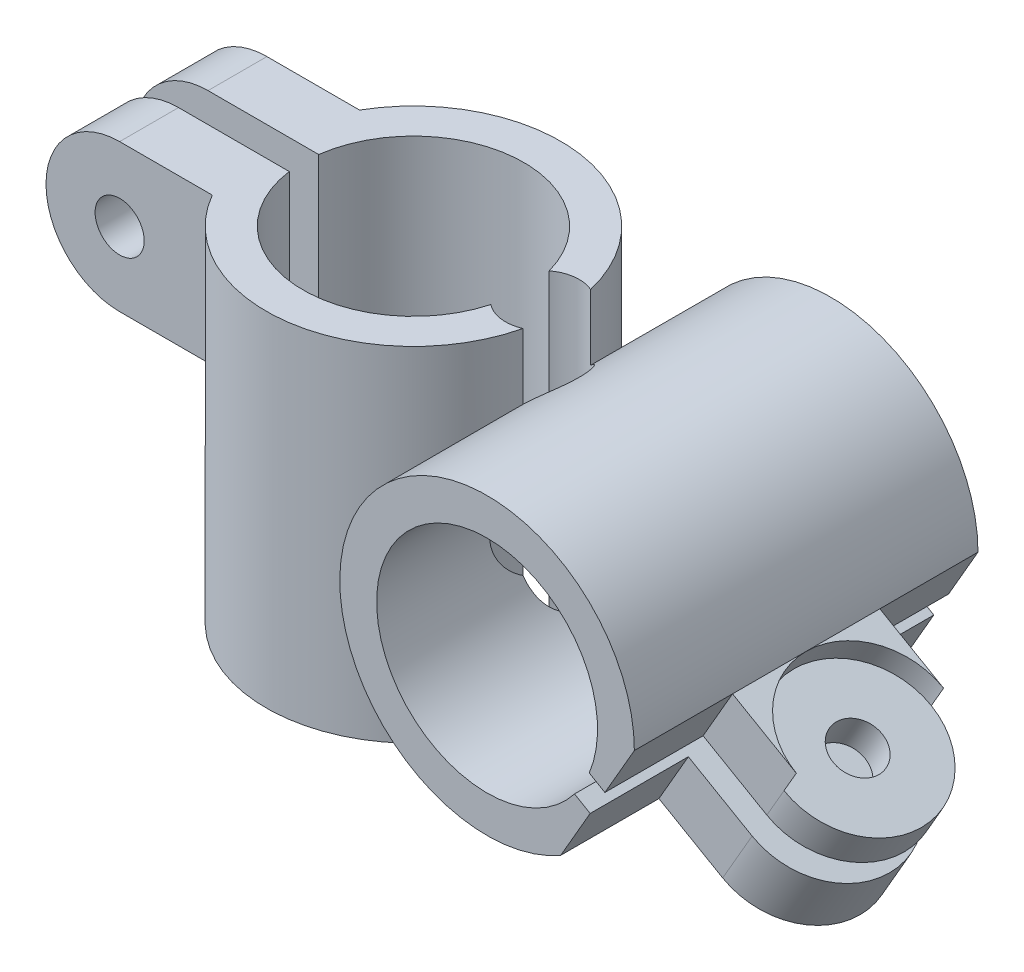
SolidWorks part; units mm, degrees
ref_plane "Front Plane" through (0, 0, 0) normal (0, 0, 1) x (1, 0, 0)
ref_plane "Top Plane" through (0, 0, 0) normal (0, 1, 0) x (1, 0, 0)
ref_plane "Right Plane" through (0, 0, 0) normal (1, 0, 0) x (0, 0, -1)
sketch "Sketch2" plane through (0, 0, 0) normal (0, 1, 0) x (1, 0, 0)
  line L0 (-34.709, 0) -> (31.8786, 0) construction
  line L1 (-29.8496, 3) -> (-22.2991, 3)
  line L2 (-29.8496, -3) -> (-22.2991, -3)
  arc A0 (-22.2991, -3) -> (21.6964, -5.9594) centre (0, 0) ccw
  circle A1 centre (0, 0) radius 26.25 construction
  arc A2 (-29.8496, -3) -> (29.1964, -6.897) centre (0, 0) ccw
  arc A3 (21.6964, -5.9594) -> (29.1964, -6.897) centre (26.25, 0) ccw
  arc A4 (21.6964, 5.9594) -> (-22.2991, 3) centre (0, 0) ccw
  arc A5 (29.1964, 6.897) -> (21.6964, 5.9594) centre (26.25, 0) ccw
  arc A6 (29.1964, 6.897) -> (-29.8496, 3) centre (0, 0) ccw
  dimension "D1" = 45
  dimension "D2" = 52.5
  dimension "D3" = 60
  dimension "D4" = 15
  dimension "D5" = 6
  dimension "D6" = 3
extrude "Boss-Extrude1" add sketch "Sketch2" along normal blind 70
sketch "Sketch3" plane through (0, 0, -3) normal (0, 0, 1) x (1, 0, 0)
  line L0 (-29.8496, 70) -> (-44.8496, 70)
  line L1 (-29.8496, 40) -> (-44.8496, 40)
  line L2 (-29.8496, 70) -> (-29.8496, 0) construction
  line L3 (-29.8496, 70) -> (-29.8496, 40)
  arc A0 (-44.8496, 40) -> (-44.8496, 70) centre (-44.8496, 55) cw
  circle A1 centre (-44.8496, 55) radius 5
  dimension "D1" = 15
  dimension "D3" = 10
  dimension "D2" = 15
extrude "Boss-Extrude3" add sketch "Sketch3" against normal blind 12 separate body
sketch "Sketch4" plane through (0, 0, 3) normal (0, 0, -1) x (-1, 0, 0)
  line L0 (29.8496, 40) -> (29.8496, 70) construction
  line L1 (44.8496, 40) -> (29.8496, 40) construction
  line L2 (29.8496, 70) -> (44.8496, 70) construction
  line L3 (29.8496, 40) -> (29.8496, 70)
  line L4 (44.8496, 40) -> (29.8496, 40)
  line L5 (29.8496, 70) -> (44.8496, 70)
  arc A0 (44.8496, 40) -> (44.8496, 70) centre (44.8496, 55) ccw construction
  arc A1 (44.8496, 40) -> (44.8496, 70) centre (44.8496, 55) ccw
  circle A2 centre (44.8496, 55) radius 5 construction
  circle A3 centre (44.8496, 55) radius 5
extrude "Boss-Extrude4" add sketch "Sketch4" against normal blind 12 separate body
sketch "Sketch5" plane through (-29.8496, 0, 0) normal (1, 0, 0) x (0, 0, -1)
  line L4 (-3, 40) -> (-3, 70)
  line L5 (-3, 70) -> (-15, 70)
  line L6 (-15, 70) -> (-15, 40)
  line L7 (-15, 40) -> (-3, 40)
  line L8 (-3, 40) -> (-3, 70)
  line L9 (-3, 70) -> (-15, 70)
  line L10 (-15, 70) -> (-15, 40)
  line L11 (-15, 40) -> (-3, 40)
  dimension "D1" = 0
extrude "Boss-Extrude5" add sketch "Sketch5" along normal up to next
sketch "Sketch6" plane through (-29.8496, 0, 0) normal (1, 0, 0) x (0, 0, -1)
  line L4 (3, 70) -> (3, 40)
  line L5 (3, 40) -> (15, 40)
  line L6 (15, 40) -> (15, 70)
  line L7 (15, 70) -> (3, 70)
  line L8 (3, 70) -> (3, 40)
  line L9 (3, 40) -> (15, 40)
  line L10 (15, 40) -> (15, 70)
  line L11 (15, 70) -> (3, 70)
  dimension "D1" = 0
extrude "Boss-Extrude6" add sketch "Sketch6" along normal up to next
sketch "Sketch7" plane through (0, 0, 0) normal (0, 0, 1) x (1, 0, 0)
  line L0 (50, 35) -> (98.4808, 7.0096) construction
  line L1 (-29.8496, 0) -> (29.1964, 0) construction
  line L2 (20, 35) -> (80, 35) construction
  line L3 (99.9808, 9.6077) -> (70.8116, 26.4485)
  line L4 (96.9808, 4.4115) -> (67.8116, 21.2524)
  line L5 (99.9808, 9.6077) -> (105.9808, 20)
  line L6 (105.9808, 20) -> (80, 35)
  line L7 (96.9808, 4.4115) -> (90.9808, -5.9808)
  line L8 (90.9808, -5.9808) -> (65, 9.0192)
  arc A0 (80, 35) -> (65, 9.0192) centre (50, 35) ccw
  arc A1 (70.8116, 26.4485) -> (67.8116, 21.2524) centre (50, 35) ccw
  point P13 (0, 0)
  point P18 (98.1379, 7.2076)
  point P19 (98.4552, 7.0244)
  dimension "D1" = 60
  dimension "D2" = 45
  dimension "D3" = 50
  dimension "D4" = 35
  dimension "D5" = 30
  dimension "D6" = 6
  dimension "D7" = 3
  dimension "D8" = 30
  dimension "D9" = 15
  dimension "D10" = 30
extrude "Boss-Extrude7" add sketch "Sketch7" along normal blind 35 and the other way blind 35
sketch "Sketch8" plane through (0, 0, 0) normal (0, 1, 0) x (1, 0, 0)
  circle A0 centre (26.25, 0) radius 7.5
  dimension "D1" = 15
extrude "Cut-Extrude1" cut sketch "Sketch8" along normal through all
sketch "Sketch9" plane through (35.1554, 60.891, 0) normal (0.5, 0.866, 0) x (0.866, -0.5, 0)
  line L0 (66.782, 15) -> (51.782, 15)
  line L1 (51.782, 35) -> (51.782, -35) construction
  line L2 (66.782, -15) -> (51.782, -15)
  line L3 (81.782, 35) -> (81.782, -35) construction
  line L4 (51.782, 15) -> (51.782, -15)
  line L5 (81.782, 35) -> (51.782, 35) construction
  arc A0 (66.782, -15) -> (66.782, 15) centre (66.782, 0) ccw
  dimension "D1" = 30
  dimension "D2" = 35
sketch "Sketch10" plane through (35.1554, 60.891, 0) normal (0.5, 0.866, 0) x (0.866, -0.5, 0)
  line L1 (66.782, 15) -> (51.782, 15) construction
  line L3 (66.782, 15) -> (51.782, 15)
  line L4 (51.782, 15) -> (51.782, 35)
  line L5 (51.782, 35) -> (81.782, 35)
  line L6 (81.782, 35) -> (81.782, 0)
  arc A0 (66.782, -15) -> (66.782, 15) centre (66.782, 0) ccw construction
  arc A1 (81.782, 0) -> (66.782, 15) centre (66.782, 0) ccw
extrude "Cut-Extrude4" cut sketch "Sketch10" against normal through all
sketch "Sketch11" plane through (35.1554, 60.891, 0) normal (0.5, 0.866, 0) x (0.866, -0.5, 0)
  line L0 (66.782, -15) -> (51.782, -15) construction
  line L1 (66.782, -15) -> (51.782, -15)
  line L4 (66.782, 15) -> (51.782, 15)
  line L5 (51.782, 15) -> (51.782, -35)
  line L6 (51.782, -35) -> (81.782, -35)
  line L7 (81.782, -35) -> (81.782, 0)
  line L9 (51.782, -15) -> (51.782, -35)
  line L10 (51.782, -35) -> (81.782, -35)
  line L11 (81.782, -35) -> (81.782, 0)
  arc A0 (66.782, -15) -> (66.782, 15) centre (66.782, 0) ccw construction
  arc A1 (81.782, 0) -> (66.782, 15) centre (66.782, 0) ccw
  arc A3 (66.782, -15) -> (81.782, 0) centre (66.782, 0) ccw
  dimension "D1" = 0
extrude "Cut-Extrude5" cut sketch "Sketch11" against normal through all
sketch "Sketch12" plane through (35.1554, 60.891, 0) normal (0.5, 0.866, 0) x (0.866, -0.5, 0)
  circle A0 centre (66.782, 0) radius 15
  dimension "D1" = 30
extrude "Cut-Extrude6" cut sketch "Sketch12" against normal blind 5
sketch "Sketch13" plane through (32.6554, 56.5609, 0) normal (0.5, 0.866, 0) x (0.866, -0.5, 0)
  circle A0 centre (66.782, 0) radius 5
  dimension "D1" = 10
extrude "Cut-Extrude7" cut sketch "Sketch13" against normal through all
sketch "Sketch16" plane through (0, 0, 0) normal (0, 0, 1) x (1, 0, 0)
  line L0 (50, 5) -> (29.1964, 5)
  line L1 (29.1964, 13.3849) -> (29.1964, 0) construction
  line L2 (29.1964, 5) -> (29.1964, 13.3849)
  arc A0 (80, 35) -> (65, 9.0192) centre (50, 35) ccw construction
  arc A1 (29.1964, 13.3849) -> (50, 5) centre (50, 35) ccw
ref_plane "Plane1" through (0, 65, 0) normal (0, 1, 0) x (1, 0, 0)
sketch "Sketch17" plane through (0, 65, 0) normal (0, 1, 0) x (1, 0, 0)
  line L0 (20, 0) -> (50, 0)
  line L1 (50, 0) -> (29.1964, 0) construction
  line L2 (29.1964, 0) -> (50, 0) construction
  line L3 (20, -4.1458) -> (20, -10.3077) construction
